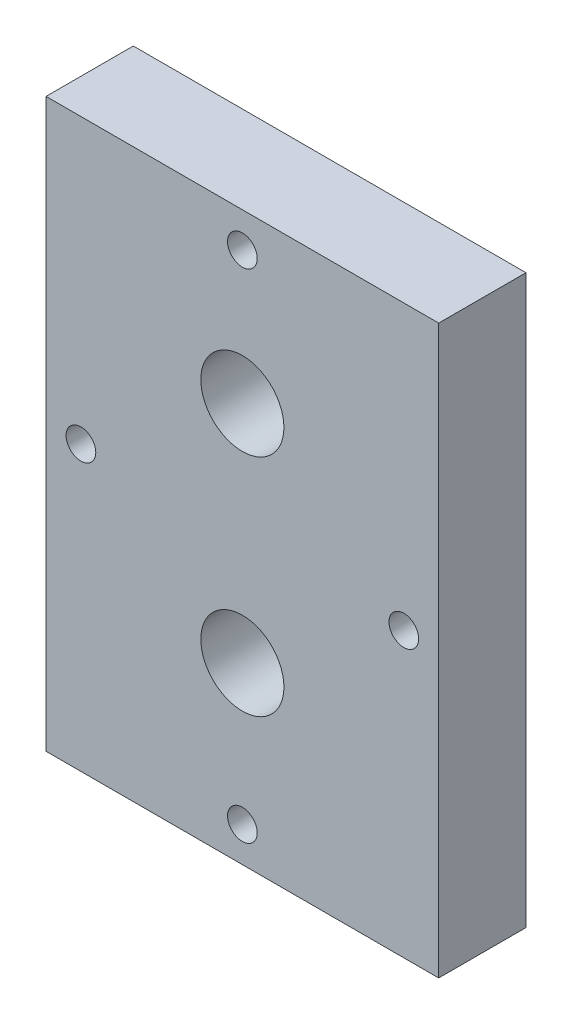
SolidWorks part; units mm, degrees
material "Náilon 6/10"
ref_plane "Plano frontal" through (0, 0, 0) normal (0, 0, 1) x (1, 0, 0)
ref_plane "Plano superior" through (0, 0, 0) normal (0, 1, 0) x (1, 0, 0)
ref_plane "Plano direito" through (0, 0, 0) normal (1, 0, 0) x (0, 0, -1)
sketch "Esboço2" plane through (0, 0, 0) normal (0, 0, 1) x (1, 0, 0)
  line L1 (-41.7829, 155.7324) -> (3.2171, 155.7324)
  line L2 (-41.7829, 155.7324) -> (-41.7829, 90.7324)
  line L3 (-41.7829, 90.7324) -> (3.2171, 90.7324)
  line L4 (3.2171, 155.7324) -> (3.2171, 90.7324)
  dimension "D1" = 45
  dimension "D2" = 65
extrude "Ressalto-extrusão2" add sketch "Esboço2" against normal blind 10
sketch "Esboço3" plane through (0, 0, 0) normal (0, 0, 1) x (1, 0, 0)
  line L0 (-41.7829, 155.7324) -> (-41.7829, 90.7324) construction
  line L1 (-41.7829, 90.7324) -> (3.2171, 90.7324) construction
  circle A0 centre (-19.2829, 136.5024) radius 4.7625
  circle A1 centre (-19.2829, 110.7324) radius 4.7625
  dimension "D1" = 9.525
  dimension "D2" = 9.525
  dimension "D3" = 22.5
  dimension "D4" = 22.5
  dimension "D5" = 20
  dimension "D6" = 45.77
extrude "Corte-extrusão1" cut sketch "Esboço3" against normal through all
hole_wizard "Furo com folga de M31" positions "Esboço5" profile "Esboço4" hole size "M3" standard "Métrico Ansi" end condition up to next
sketch "Esboço5" plane through (0.1605, 1.1735, -10) normal (0, 0, -1) x (-1, 0, 0)
  line L0 (-3.0567, 154.5589) -> (41.9433, 154.5589) construction
  line L1 (-3.0567, 154.5589) -> (41.9433, 154.5589) construction
  line L2 (-3.0567, 89.5589) -> (-3.0567, 154.5589) construction
  line L4 (41.9433, 89.5589) -> (-3.0567, 89.5589) construction
  line L5 (41.9433, 154.5589) -> (41.9433, 89.5589) construction
  point P0 (19.4433, 93.5589)
  point P1 (19.4433, 150.5589)
  point P3 (0.9433, 122.0589)
  point P6 (37.9433, 122.0589)
  dimension "D1" = 4
  dimension "D2" = 4
  dimension "D3" = 4
  dimension "D4" = 4
  dimension "D5" = 22.5
  dimension "D6" = 22.5
  dimension "D7" = 32.5
  dimension "D8" = 32.5
sketch "Esboço4" plane through (-19.2829, 94.7324, -10) normal (1, 0, 0) x (0, 1, 0)
  line L0 (0, 0) -> (0, 10)
  line L1 (0, 10) -> (1.7, 10)
  line L2 (1.7, 10) -> (1.7, 0)
  line L5 (1.7, 0) -> (0, 0)
  line L11 (0, -6.35) -> (0, 107.95) construction
  dimension "Thru Hole Dia." = 3.4
  dimension "Thru Hole Depth" = 10
sketch "Esboço6" plane through (0, 0, -10) normal (0, 0, -1) x (-1, 0, 0)
  circle A0 centre (0.7829, 123.2324) radius 3.75
  dimension "D1" = 7.5
extrude "Corte-extrusão2" cut sketch "Esboço6" against normal blind 2.45
